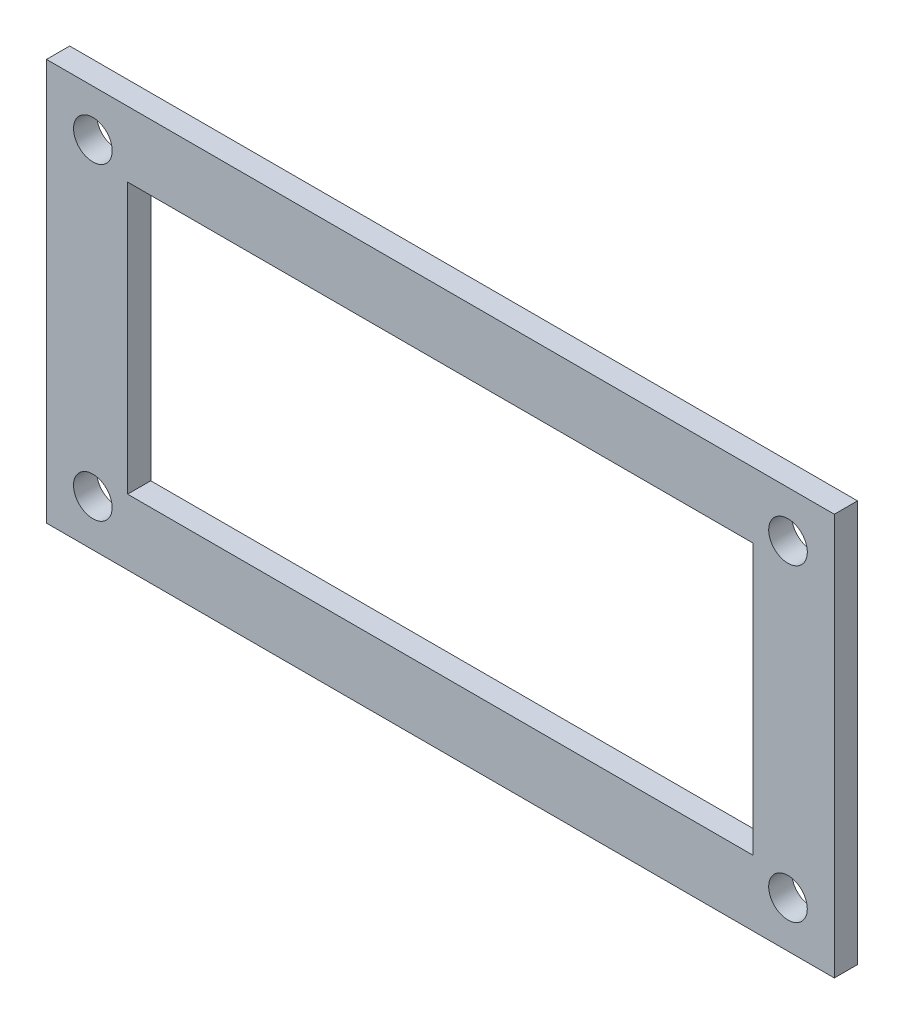
SolidWorks part; units mm, degrees
ref_plane "Front Plane" through (0, 0, 0) normal (0, 0, 1) x (1, 0, 0)
ref_plane "Top Plane" through (0, 0, 0) normal (0, 1, 0) x (1, 0, 0)
ref_plane "Right Plane" through (0, 0, 0) normal (1, 0, 0) x (0, 0, -1)
sketch "Sketch1" plane through (0, 0, 0) normal (0, 0, 1) x (1, 0, 0)
  line L1 (-40.5, -17.5) -> (40.5, -17.5)
  line L2 (-40.5, -17.5) -> (-40.5, 17.5)
  line L3 (-40.5, 17.5) -> (40.5, 17.5)
  line L4 (40.5, -17.5) -> (40.5, 17.5)
  line L5 (-40.5, -17.5) -> (40.5, 17.5) construction
  line L6 (-40.5, 17.5) -> (40.5, -17.5) construction
  line L7 (-51, -26) -> (51, -26)
  line L8 (-51, -26) -> (-51, 26)
  line L9 (-51, 26) -> (51, 26)
  line L10 (51, -26) -> (51, 26)
  line L11 (-51, -26) -> (51, 26) construction
  line L12 (-51, 26) -> (51, -26) construction
  line L13 (0, 0) -> (0, 59.6215) construction
  line L14 (-30.0358, 0) -> (28.3402, 0) construction
  circle A0 centre (-45, 20) radius 2.5
  circle A1 centre (-45, -20) radius 2.5
  circle A2 centre (45, -20) radius 2.5
  circle A3 centre (45, 20) radius 2.5
  point P0 (0, 0)
  point P6 (0, 0)
  dimension "D5" = 5
  dimension "D1" = 81
  dimension "D2" = 35
  dimension "D3" = 102
  dimension "D4" = 52
  dimension "D6" = 6
  dimension "D7" = 6
extrude "Boss-Extrude1" add sketch "Sketch1" along normal blind 3
